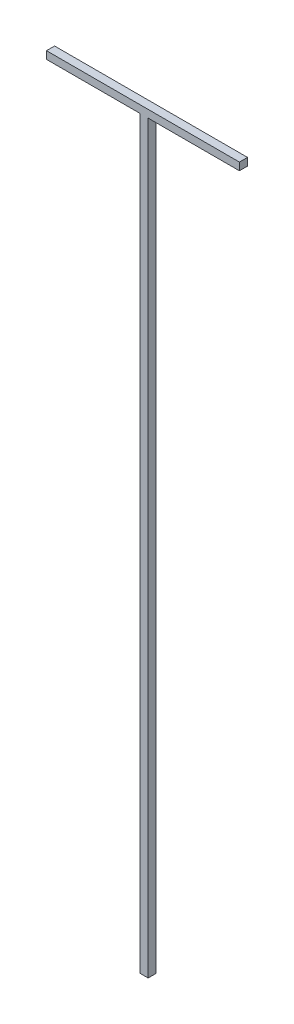
SolidWorks part; units mm, degrees
ref_plane "Спереди" through (0, 0, 0) normal (0, 0, 1) x (1, 0, 0)
ref_plane "Сверху" through (0, 0, 0) normal (0, 1, 0) x (1, 0, 0)
ref_plane "Справа" through (0, 0, 0) normal (1, 0, 0) x (0, 0, -1)
sketch "Эскиз1" plane through (0, 0, 0) normal (0, 0, 1) x (1, 0, 0)
  line L1 (-65.3526, 40.8454) -> (172.7176, 40.8454)
  line L2 (-65.3526, 40.8454) -> (-65.3526, 31.5093)
  line L3 (-65.3526, 31.5093) -> (172.7176, 31.5093)
  line L4 (172.7176, 40.8454) -> (172.7176, 31.5093)
  line L5 (50.0968, 31.5093) -> (60.0968, 31.5093)
  line L6 (50.0968, 31.5093) -> (50.0968, -887.4478)
  line L7 (50.0968, -887.4478) -> (60.0968, -887.4478)
  line L8 (60.0968, 31.5093) -> (60.0968, -887.4478)
  point P8 (0, 0)
  point P9 (0, 0)
extrude "Бобышка-Вытянуть1" add sketch "Эскиз1" along normal blind 10 contours L6 L7 L8 L5 | L3 L4 L1 L2
